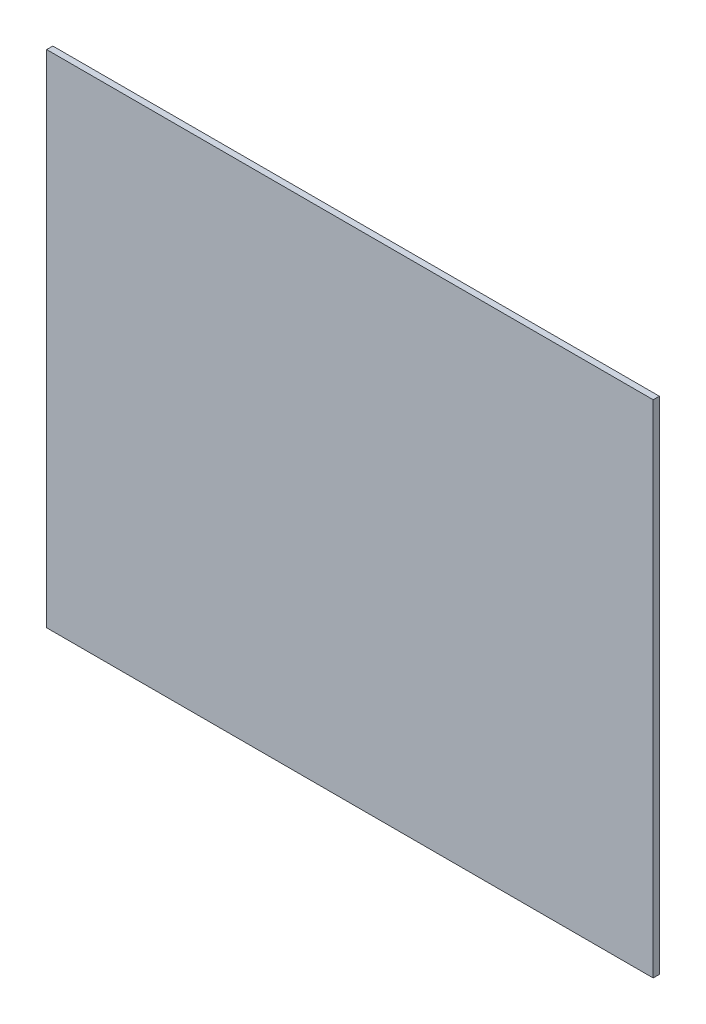
SolidWorks part; units mm, degrees
ref_plane "Front Plane" through (0, 0, 0) normal (0, 0, 1) x (1, 0, 0)
ref_plane "Top Plane" through (0, 0, 0) normal (0, 1, 0) x (1, 0, 0)
ref_plane "Right Plane" through (0, 0, 0) normal (1, 0, 0) x (0, 0, -1)
sketch "Sketch1" plane through (0, 0, 0) normal (0, 0, 1) x (1, 0, 0)
  line L0 (8.2291, 20) -> (8.2291, -290) construction
  line L1 (8.2291, -276.4405) -> (303.2291, -276.4405)
  line L2 (8.2291, -276.4405) -> (8.2291, -520)
  line L3 (8.2291, -520) -> (303.2291, -520)
  line L4 (303.2291, -276.4405) -> (303.2291, -520)
extrude "Boss-Extrude1" add sketch "Sketch1" along normal blind 3
